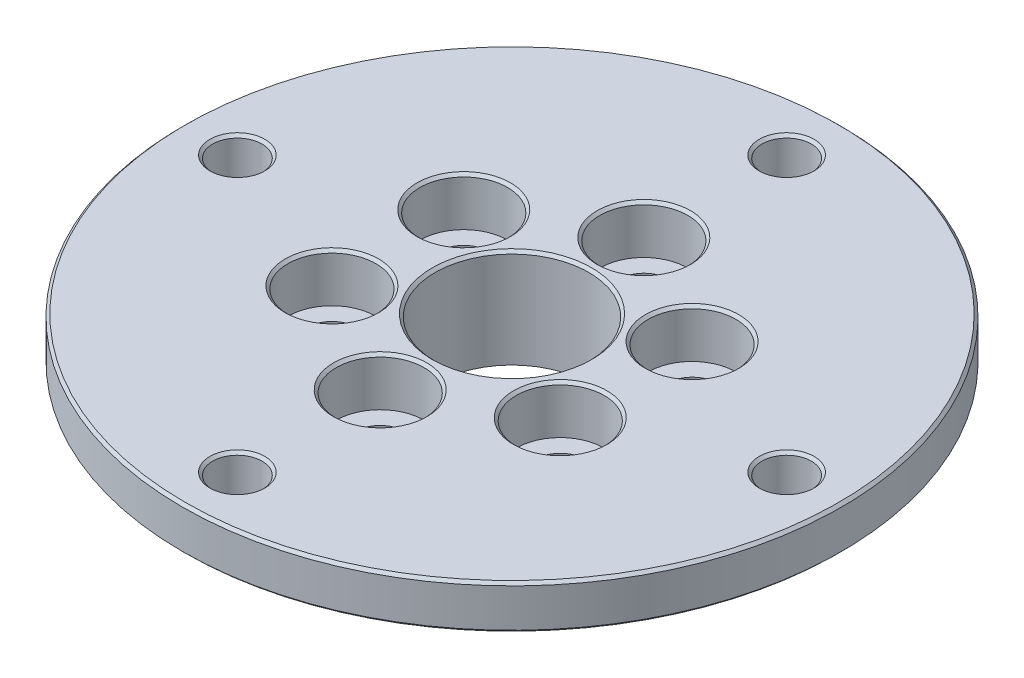
SolidWorks part; units mm, degrees
material "1.0037 (S235JR)"
ref_plane "Ebene vorne" through (0, 0, 0) normal (0, 0, 1) x (1, 0, 0)
ref_plane "Ebene oben" through (0, 0, 0) normal (0, 1, 0) x (1, 0, 0)
ref_plane "Ebene rechts" through (0, 0, 0) normal (1, 0, 0) x (0, 0, -1)
sketch "Skizze1" plane through (0, 0, 0) normal (0, 1, 0) x (1, 0, 0)
  circle A0 centre (0, 0) radius 7
  circle A1 centre (0, 0) radius 20.5
  dimension "D1" = 14
  dimension "D2" = 41
extrude "Aufsatz-Linear austragen1" add sketch "Skizze1" along normal blind 5
sketch "Skizze3" plane through (0, 5, 0) normal (0, 1, 0) x (1, 0, 0)
  circle A1 centre (0, 0) radius 30
  circle A2 centre (0, 0) radius 7 construction
  circle A3 centre (0, 0) radius 7
  dimension "D1" = 60
extrude "Aufsatz-Linear austragen2" add sketch "Skizze3" along normal blind 4
hole_wizard "Durchgangsloch für M41" positions "Skizze4" profile "Skizze5" hole size "M4" standard "ANSI Metrisch" end condition through all
sketch "Skizze4" plane through (0, 5, 0) normal (0, -1, 0) x (-1, 0, 0)
  circle A0 centre (0, 0) radius 25 construction
  point P0 (0, 25)
  point P8 (-25, 0)
  point P10 (0, -25)
  point P12 (25, 0)
  dimension "D1" = 50
sketch "Skizze5" plane through (0, 5, -25) normal (1, 0, 0) x (0, 0, -1)
  line L0 (0, 0) -> (0, 4)
  line L1 (0, 4) -> (2.25, 4)
  line L2 (2.25, 4) -> (2.25, 0)
  line L5 (2.25, 0) -> (0, 0)
  line L11 (0, -6.35) -> (0, 107.95) construction
  dimension "Bohrerdurchmesser" = 4.5
  dimension "Bohrungstiefe" = 4
hole_wizard "Stirnsenkung für M4 Zylinderschraube mit Innensechskant1" positions "Skizze7" profile "Skizze8" counterbore size "M4" standard "DIN" end condition through all
sketch "Skizze7" plane through (0, 9, 0) normal (0, 1, 0) x (1, 0, 0)
  circle A0 centre (0, 0) radius 12 construction
  point P5 (0, 12)
  point P12 (10.3923, 6)
  point P13 (10.3923, -6)
  point P14 (0, -12)
  point P15 (-10.3923, -6)
  point P16 (-10.3923, 6)
  dimension "D1" = 24
  dimension "D2" = 6
sketch "Skizze8" plane through (-10.3923, 9, -6) normal (1, 0, 0) x (0, 0, 1)
  line L0 (0, 0) -> (0, 9)
  line L1 (0, 9) -> (2.25, 9)
  line L3 (2.25, 9) -> (2.25, 4.4)
  line L4 (2.25, 4.4) -> (4, 4.4)
  line L5 (4, 4.4) -> (4, 0)
  line L7 (4, 0) -> (0, 0)
  line L11 (0, -6.35) -> (0, 107.95) construction
  dimension "Bohrerdurchmesser" = 4.5
  dimension "Bohrungstiefe" = 9
  dimension "Senkdurchmesser2" = 8
  dimension "Senktiefe2" = 4.4
chamfer "Fase1" distance 0.25 angle 45 18 edges at (0, 9, -8) (10.3923, 9, -2) (10.3923, 9, 10) (0, 9, 16) (-10.3923, 9, 10) (-10.3923, 9, -2) (0, 5, -27.25) (0, 9, -27.25) (25, 5, -2.25) (25, 9, -2.25) (0, 5, 22.75) (0, 9, 22.75) (-25, 5, -2.25) (-25, 9, -2.25) (0, 9, 7) (0, 5, 30) (0, 5, 20.5) (0, 9, 30)
